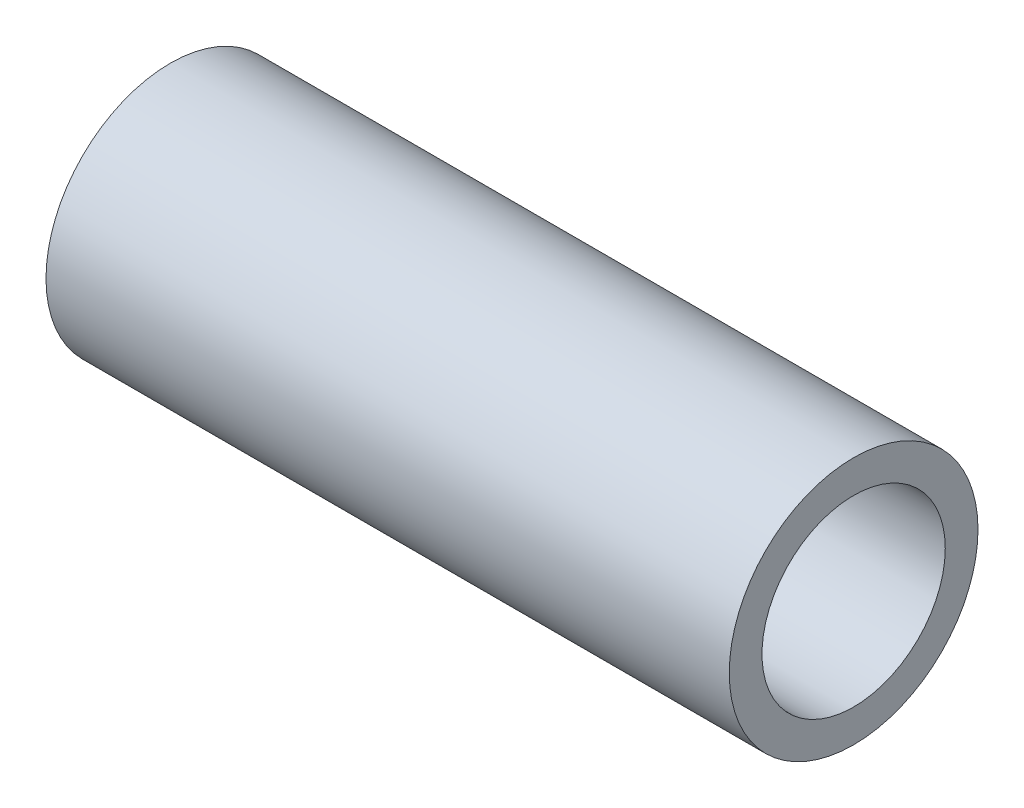
SolidWorks part; units mm, degrees
ref_plane "Front Plane" through (0, 0, 0) normal (0, 0, 1) x (1, 0, 0)
ref_plane "Top Plane" through (0, 0, 0) normal (0, 1, 0) x (1, 0, 0)
ref_plane "Right Plane" through (0, 0, 0) normal (1, 0, 0) x (0, 0, -1)
sketch "Sketch1" plane through (0, 0, 0) normal (1, 0, 0) x (0, 0, -1)
  circle A0 centre (0, 0) radius 7.112
  circle A1 centre (0, 0) radius 9.652
  dimension "D1" = 2.54
  dimension "D2" = 14.224
extrude "Boss-Extrude1" add sketch "Sketch1" along normal blind 53.0276
